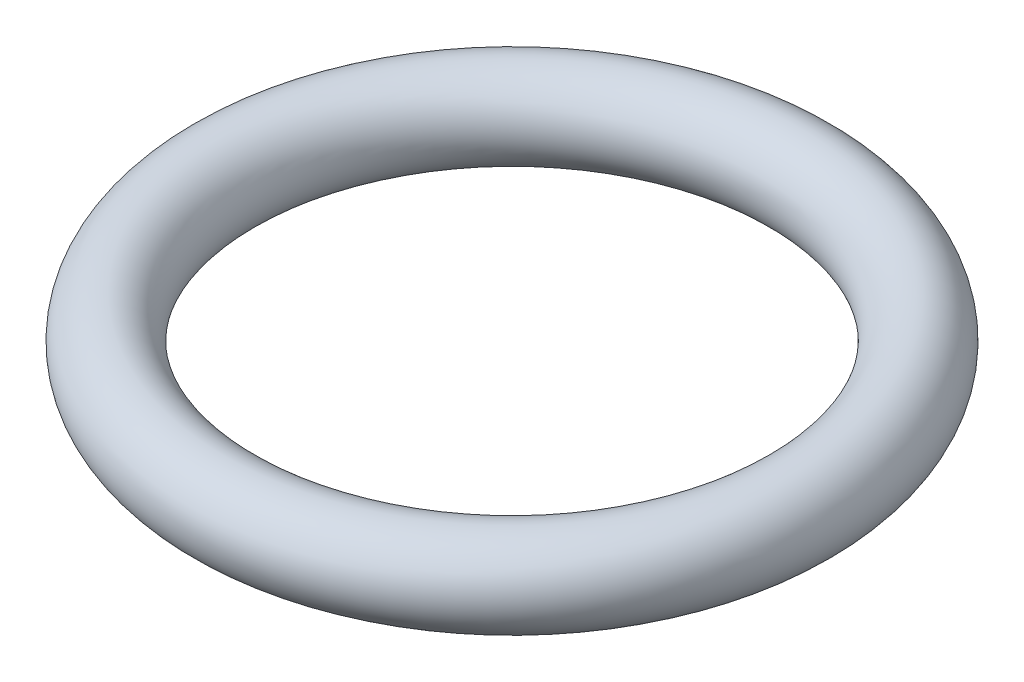
SolidWorks part; units mm, degrees
ref_plane "Front" through (0, 0, 0) normal (0, 0, 1) x (1, 0, 0)
ref_plane "Top" through (0, 0, 0) normal (0, 1, 0) x (1, 0, 0)
ref_plane "Right" through (0, 0, 0) normal (1, 0, 0) x (0, 0, -1)
sketch "Sketch1" plane through (0, 0, 0) normal (0, 0, 1) x (1, 0, 0)
  line L0 (0, -68.3404) -> (0, 3348.6778) construction
  circle A0 centre (5.3848, 0) radius 0.7938
  point P5 (0, 0)
  dimension "D1" = 1.5875
  dimension "D2" = 5.3848
revolve "Revolve1" add sketch "Sketch1" angle 360 about L0
